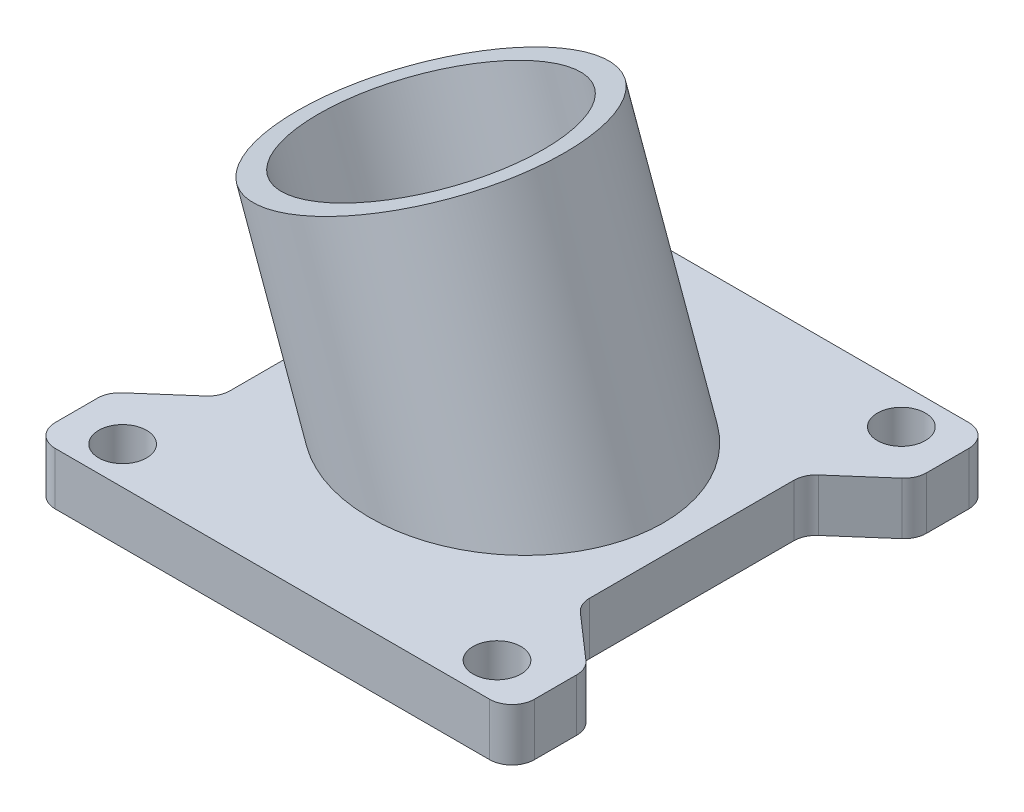
SolidWorks part; units mm, degrees
ref_plane "Front Plane" through (0, 0, 0) normal (0, 0, 1) x (1, 0, 0)
ref_plane "Top Plane" through (0, 0, 0) normal (0, 1, 0) x (1, 0, 0)
ref_plane "Right Plane" through (0, 0, 0) normal (1, 0, 0) x (0, 0, -1)
sketch "Sketch1" plane through (0, 0, 0) normal (0, 1, 0) x (1, 0, 0)
  line L0 (-12, 0) -> (-12, 7.5)
  line L1 (-12, 7.5) -> (-16, 11)
  line L2 (-16, 11) -> (-16, 16)
  line L3 (-16, 16) -> (16, 16)
  line L8 (-12, 0) -> (12, 0)
  line L9 (0, 16) -> (0, 0) construction
  line L10 (16, 11) -> (16, 16)
  line L11 (12, 7.5) -> (16, 11)
  line L12 (12, 0) -> (12, 7.5)
  dimension "D1" = 32
  dimension "D2" = 16
  dimension "D3" = 5
  dimension "D4" = 7.5
  dimension "D5" = 24
extrude "Boss-Extrude1" add sketch "Sketch1" along normal blind 3.5
sketch "Sketch2" plane through (0, 3.5, 0) normal (0, 1, 0) x (1, 0, 0)
  line L0 (-16, 13.5) -> (16, 13.5) construction
  line L1 (-16, 16) -> (-16, 11) construction
  line L2 (16, 11) -> (16, 16) construction
  line L3 (0, 0) -> (0, 16) construction
  line L4 (-12, 0) -> (12, 0) construction
  line L5 (16, 16) -> (-16, 16) construction
  circle A0 centre (-12.5, 13.5) radius 1.6
  circle A2 centre (12.5, 13.5) radius 1.6
  dimension "D1" = 3.2
  dimension "D2" = 12.5
extrude "Cut-Extrude1" cut sketch "Sketch2" against normal up to next
fillet "Fillet1" radius 1.5 6 edges at (12, 1.75, -7.5) (16, 1.75, -11) (16, 1.75, -16) (-12, 1.75, -7.5) (-16, 1.75, -11) (-16, 1.75, -16)
mirror "Mirror1" about plane through (0, 0, 0) normal (0, 0, 1) of "Fillet1", "Cut-Extrude1", "Boss-Extrude1"
ref_plane "Plane2" through (-1.4037, 3.8567, 0) normal (-0.342, 0.9397, 0) x (0, 0, 1)
sketch "Sketch3" plane through (-1.4037, 3.8567, 0) normal (-0.342, 0.9397, 0) x (0, 0, 1)
  line L1 (-16, 1.1971) -> (16, 1.1971) construction
  line L2 (-16, 14.8226) -> (-16, -12.4285) construction
  line L3 (16, 14.8226) -> (16, -12.4285) construction
  circle A0 centre (0, 1.1971) radius 8
  circle A1 centre (0, 1.1971) radius 9.5
  dimension "D1" = 16
  dimension "D2" = 1.5
extrude "Boss-Extrude3" add sketch "Sketch3" along normal blind 15 and the other way up to surface other way up to face at (-12.5, 3.5, 11.9)
